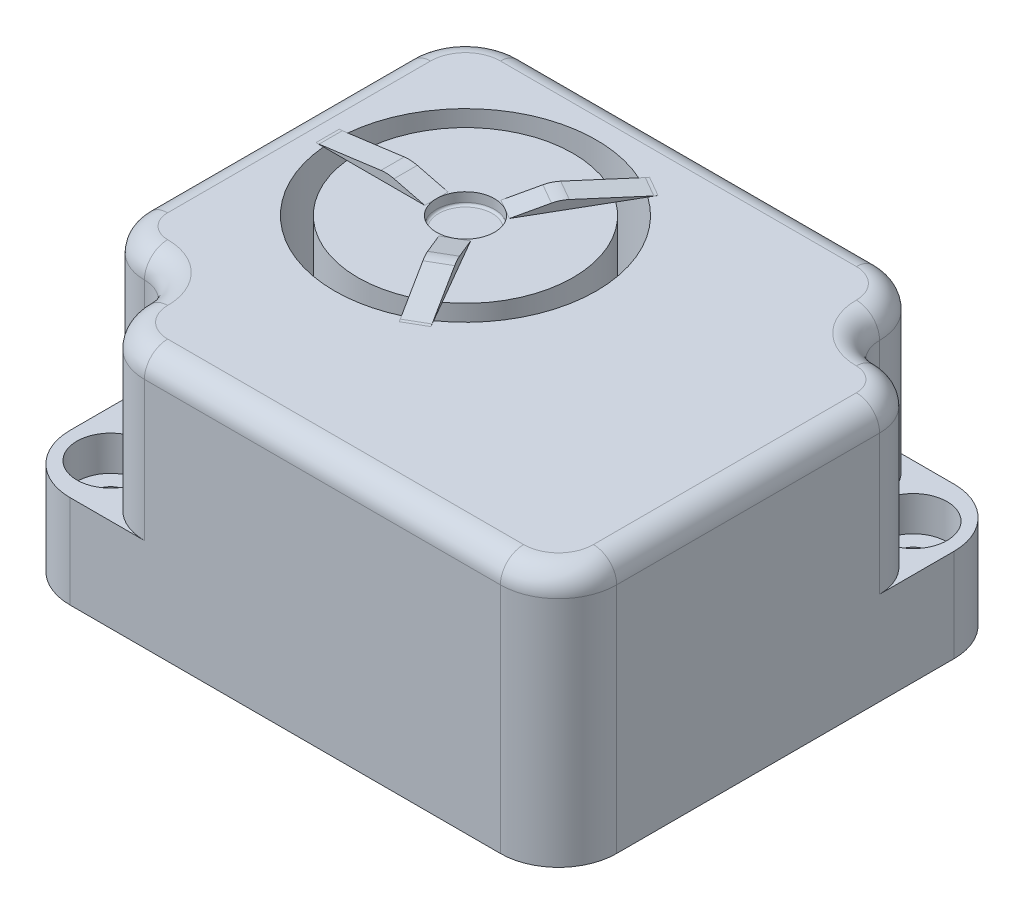
SolidWorks part; units mm, degrees
ref_plane "Plan de face" through (0, 0, 0) normal (0, 0, 1) x (1, 0, 0)
ref_plane "Plan de dessus" through (0, 0, 0) normal (0, 1, 0) x (1, 0, 0)
ref_plane "Plan de droite" through (0, 0, 0) normal (1, 0, 0) x (0, 0, -1)
sketch "Esquisse1" plane through (0, 0, 0) normal (0, 1, 0) x (1, 0, 0)
  line L1 (-23.5, -19.5) -> (23.5, -19.5)
  line L2 (-23.5, -19.5) -> (-23.5, 19.5)
  line L3 (-23.5, 19.5) -> (23.5, 19.5)
  line L4 (23.5, -19.5) -> (23.5, 19.5)
  line L5 (-23.5, -19.5) -> (23.5, 19.5) construction
  line L6 (-23.5, 19.5) -> (23.5, -19.5) construction
  point P0 (0, 0)
  dimension "D1" = 47
  dimension "D2" = 39
extrude "Boss.-Extru.1" add sketch "Esquisse1" along normal blind 22
hole_wizard "Chambrage pour vis à tête ronde bombée M31" positions "Esquisse3" profile "Esquisse4" counterbore size "M3" standard "ISO" end condition through all
sketch "Esquisse3" plane through (0, 22, 0) normal (0, 1, 0) x (1, 0, 0)
  line L0 (0, 8.3031) -> (0, 0) construction
  line L1 (0, 0) -> (11.7744, 0) construction
  point P0 (-19.5, -15)
  point P2 (19.5, 15)
  dimension "D1" = 30
  dimension "D2" = 39
  dimension "D3" = 19.5
  dimension "D4" = 15
sketch "Esquisse4" plane through (-19.5, 22, 15) normal (1, 0, 0) x (0, 0, 1)
  line L0 (0, 0) -> (0, 22)
  line L1 (0, 22) -> (1.5, 22)
  line L3 (1.5, 22) -> (1.5, 17)
  line L4 (1.5, 17) -> (2.9, 17)
  line L5 (2.9, 17) -> (2.9, 0)
  line L7 (2.9, 0) -> (0, 0)
  line L11 (0, -6.35) -> (0, 107.95) construction
  dimension "Diamètre du perçage jusqu'au prochain" = 3
  dimension "Profondeur du perçage jusqu'au prochain" = 22
  dimension "Diamètre du chambrage" = 5.8
  dimension "Profondeur du chambrage" = 17
sketch "Esquisse5" plane through (0, 22, 0) normal (0, 1, 0) x (1, 0, 0)
  line L0 (-23.5, 19.5) -> (-23.5, -19.5) construction
  line L1 (-23.5, -19.5) -> (23.5, -19.5) construction
  line L2 (-23.5, -8.1) -> (-23.5, -19.5)
  line L3 (-23.5, -19.5) -> (-12.1, -19.5)
  line L4 (-19.5, -9.6361) -> (-19.5, -15) construction
  line L5 (-19.5, -15) -> (-13.9251, -15) construction
  line L6 (23.5, 8.1) -> (23.5, 19.5)
  line L7 (23.5, 19.5) -> (12.1, 19.5)
  arc A0 (-23.5, -8.1) -> (-19.5, -12.1) centre (-19.5, -8.1) ccw
  arc A1 (-16.6, -15) -> (-12.1, -19.5) centre (-12.1, -15) ccw
  circle A2 centre (-19.5, -15) radius 2.9 construction
  arc A3 (-16.6, -15) -> (-19.5, -12.1) centre (-19.5, -15) ccw
  arc A4 (23.5, 8.1) -> (19.5, 12.1) centre (19.5, 8.1) ccw
  arc A5 (16.6, 15) -> (19.5, 12.1) centre (19.5, 15) ccw
  arc A6 (16.6, 15) -> (12.1, 19.5) centre (12.1, 15) ccw
  point P23 (0, 0)
  dimension "D1" = 2
extrude "Enlèv. mat.-Extru.1" cut sketch "Esquisse5" against normal offset from surface (14 mm away) 3 up to face at (-19.5, 5, 16.5)
fillet "Congé1" radius 5 4 edges at (23.5, 4, -19.5) (23.5, 11, 19.5) (-23.5, 4, 19.5) (-23.5, 11, -19.5)
fillet "Congé2" radius 2 12 edges at (-15.282, 22, 18.182) (-17.4494, 22, 12.9494) (-22.3284, 22, 10.9284) (-23.5, 22, -3.2) (-22.0355, 22, -18.0355) (-3.2, 22, -19.5) (15.282, 22, -18.182) (17.4494, 22, -12.9494) (22.3284, 22, -10.9284) (23.5, 22, 3.2) (22.0355, 22, 18.0355) (3.2, 22, 19.5)
sketch "Esquisse6" plane through (0, 22, 0) normal (0, 1, 0) x (1, 0, 0)
  circle A0 centre (-8.5, 4.5) radius 11.25
  circle A1 centre (-8.5, 4.5) radius 9.25
  dimension "D3" = 22.5
  dimension "D4" = 18.5
  dimension "D1" = 8.5
  dimension "D2" = 4.5
extrude "Enlèv. mat.-Extru.2" cut sketch "Esquisse6" against normal blind 15
sketch "Esquisse8" plane through (0, 22, 0) normal (0, 1, 0) x (1, 0, 0)
  circle A0 centre (-8.5, 4.5) radius 2.5
  circle A1 centre (-8.5, 4.5) radius 9.25 construction
  dimension "D1" = 5
extrude "Enlèv. mat.-Extru.3" cut sketch "Esquisse8" against normal blind 1
ref_point "Point1"
ref_plane "Plan1" through (0, 0, -4.5) normal (0, 0, 1) x (1, 0, 0)
sketch "Esquisse7" plane through (0, 0, -4.5) normal (0, 0, 1) x (1, 0, 0)
  line L0 (-20.2169, 22) -> (-11, 22)
  line L1 (-11, 22) -> (-13.6414, 22.661)
  line L2 (-14.7649, 22.7245) -> (-20.2169, 22)
  line L3 (-12.1, 22) -> (18.5, 22) construction
  arc A0 (-13.6414, 22.661) -> (-14.7649, 22.7245) centre (-14.3697, 19.7507) ccw
  point P11 (-14.1971, 22.8)
  dimension "D2" = 3
  dimension "D1" = 0.8
  dimension "D3" = 5.5
extrude "Boss.-Extru.5" add sketch "Esquisse7" along normal blind 1 and the other way blind 1 contours L2 L0 L1 A0
pattern_circular "Répétition circulaire1" count 3 over 360 about axis through (-8.5, 0, -4.5) along (0, 1, 0) of "Boss.-Extru.5"
fillet "Congé3" radius 2 3 edges at (-2.6415, 22, -14.6472) (-2.6415, 22, 5.6472) (-20.2169, 22, -4.5)
fillet "Congé4" radius 0.2 1 edges at (-8.5, 21, -2)
equation "\"D3@Esquisse3\"=\"D2@Esquisse3\"/2"
equation "\"D4@Esquisse3\"=\"D1@Esquisse3\"/2"
